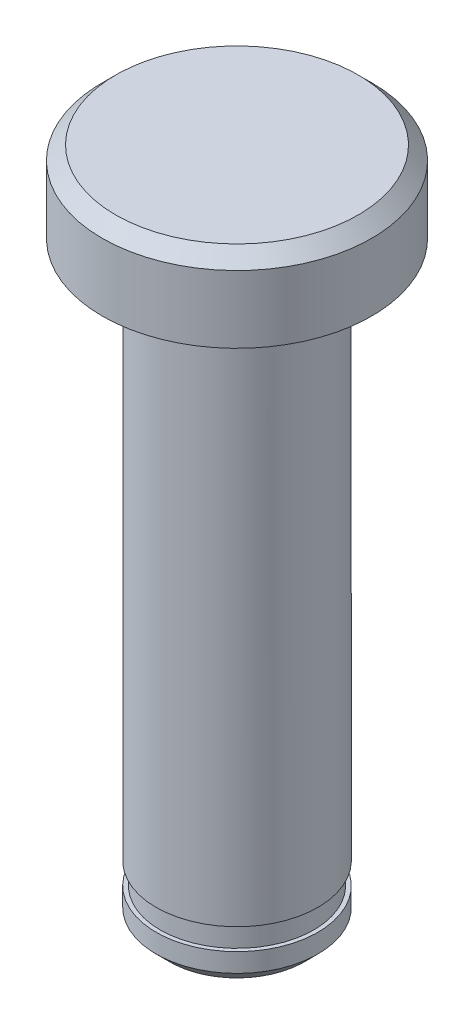
SolidWorks part; units mm, degrees
ref_plane "Front Plane" through (0, 0, 0) normal (1, 0, 0) x (0, 1, 0)
ref_plane "Top Plane" through (0, 0, 0) normal (0, 0, 1) x (0, 1, 0)
ref_plane "Right Plane" through (0, 0, 0) normal (0, 1, 0) x (-1, 0, 0)
sketch "Sketch1" plane through (0, 0, 0) normal (0, 1, 0) x (-1, 0, 0)
  circle A0 centre (0, 0) radius 5
  dimension "D1" = 10
extrude "Boss-Extrude1" add sketch "Sketch1" along normal blind 3 contours A0
chamfer "Chamfer1" distance 0.5 angle 45 1 edges at (0, 3, 5)
sketch "Sketch2" plane through (0, 0, 0) normal (0, -1, 0) x (1, 0, 0)
  circle A0 centre (0, 0) radius 3
  dimension "D1" = 6
extrude "Boss-Extrude2" add sketch "Sketch2" along normal blind 22
chamfer "Chamfer2" distance 0.5 angle 45 1 edges at (0, -22, -3)
sketch "Sketch3" plane through (0, 0, 0) normal (1, 0, 0) x (0, 1, 0)
  line L0 (-20.8, 3) -> (-20.8, 2.85)
  line L1 (0, 3) -> (-21.5, 3) construction
  line L2 (-20.8, 2.85) -> (-20, 2.85)
  line L3 (-20, 2.85) -> (-20, 3)
  line L4 (-20, 3) -> (-20, 3.35)
  line L5 (-20, 3.35) -> (-20.8, 3.35)
  line L6 (-20.8, 3.35) -> (-20.8, 3)
  line L7 (-22, 2.5) -> (-22, -2.5) construction
  line L8 (0, 0) -> (-28.4725, 0) construction
  dimension "D1" = 1.2
  dimension "D2" = 2
  dimension "D3" = 5.7
  dimension "D4" = 0.5
revolve "Cut-Revolve1" cut sketch "Sketch3" angle 360 about L8
